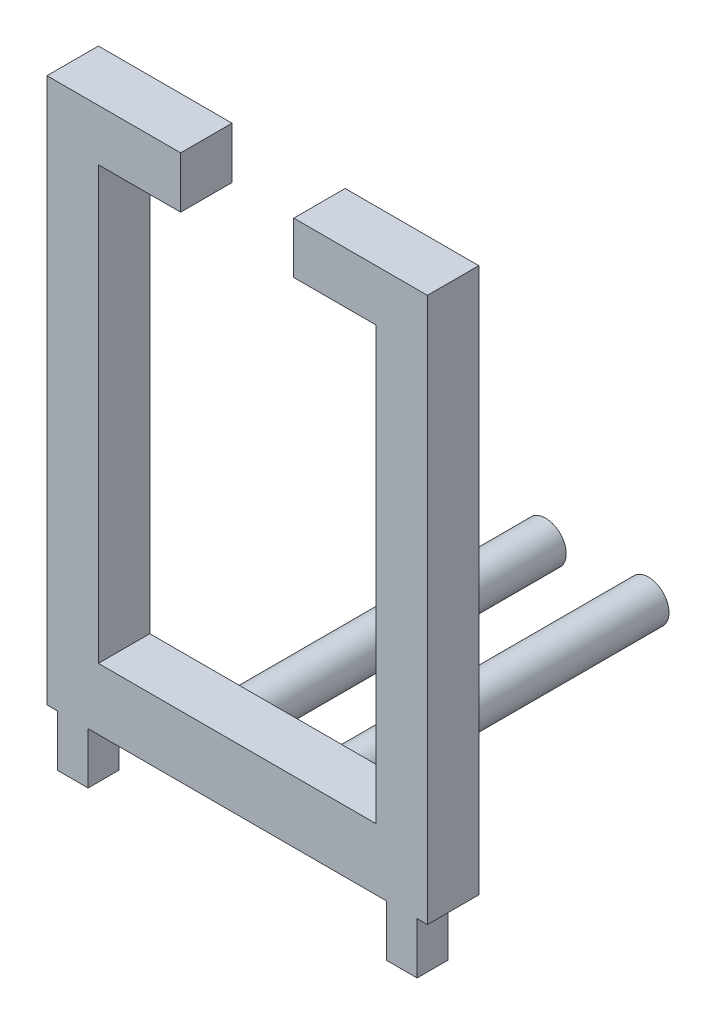
SolidWorks part; units mm, degrees
ref_plane "前视基准面" through (0, 0, 0) normal (0, 0, 1) x (1, 0, 0)
ref_plane "上视基准面" through (0, 0, 0) normal (0, 1, 0) x (1, 0, 0)
ref_plane "右视基准面" through (0, 0, 0) normal (1, 0, 0) x (0, 0, -1)
sketch "草图1" plane through (0, 0, 0) normal (0, 1, 0) x (1, 0, 0)
  line L0 (-303.1504, -31.6586) -> (-303.1504, -28.6586)
  line L1 (-303.1504, -28.6586) -> (-300.1504, -28.6586)
  line L2 (-300.1504, -28.6586) -> (-300.1504, -31.6586)
  line L3 (-300.1504, -31.6586) -> (-303.1504, -31.6586)
  line L4 (-271.1504, -28.6586) -> (-268.1504, -28.6586)
  line L5 (-268.1504, -28.6586) -> (-268.1504, -31.6586)
  line L6 (-268.1504, -31.6586) -> (-271.1504, -31.6586)
  line L7 (-271.1504, -31.6586) -> (-271.1504, -28.6586)
  point P6 (0, 0)
  point P9 (0, 0)
  dimension "D1" = 29
extrude "凸台-拉伸1" add sketch "草图1" along normal blind 5
sketch "草图2" plane through (0, 5, 0) normal (0, 1, 0) x (1, 0, 0)
  line L0 (-304.1504, -26.6586) -> (-299.1504, -26.6586)
  line L1 (-299.1504, -26.6586) -> (-299.1504, -31.6586)
  line L2 (-299.1504, -31.6586) -> (-304.1504, -31.6586)
  line L3 (-304.1504, -31.6586) -> (-304.1504, -26.6586)
  line L4 (-300.1504, -28.6586) -> (-303.1504, -28.6586) construction
  line L5 (-272.1504, -26.6586) -> (-267.1504, -26.6586)
  line L6 (-267.1504, -26.6586) -> (-267.1504, -31.6586)
  line L7 (-267.1504, -31.6586) -> (-272.1504, -31.6586)
  line L8 (-272.1504, -31.6586) -> (-272.1504, -26.6586)
  line L9 (-271.1504, -31.6586) -> (-268.1504, -31.6586) construction
  line L10 (-271.1504, -31.6586) -> (-268.1504, -31.6586) construction
  point P2 (-301.6504, -26.6586)
  point P7 (-301.6504, -28.6586)
  point P13 (-269.6504, -31.6586)
  point P17 (-269.6504, -31.6586)
extrude "凸台-拉伸2" add sketch "草图2" along normal blind 6
sketch "草图4" plane through (0, 11, 0) normal (0, 1, 0) x (1, 0, 0)
  line L0 (-304.1504, -26.6586) -> (-267.1504, -26.6586)
  line L1 (-267.1504, -26.6586) -> (-267.1504, -31.6586)
  line L2 (-267.1504, -31.6586) -> (-304.1504, -31.6586)
  line L3 (-304.1504, -31.6586) -> (-304.1504, -26.6586)
extrude "凸台-拉伸3" add sketch "草图4" against normal blind 6
sketch "草图5" plane through (0, 0, 26.6586) normal (0, 0, -1) x (-1, 0, 0)
  circle A0 centre (280.6505, 8.0197) radius 2
  circle A1 centre (290.6504, 7.9803) radius 2
  dimension "D1" = 9.9999
extrude "凸台-拉伸4" add sketch "草图5" along normal blind 30
sketch "草图6" plane through (0, 11, 0) normal (0, 1, 0) x (1, 0, 0)
  line L0 (-267.1504, -31.6586) -> (-272.1504, -31.6586)
  line L1 (-304.1504, -31.6586) -> (-267.1504, -31.6586) construction
  line L2 (-272.1504, -31.6586) -> (-272.1504, -26.6586)
  line L3 (-267.1504, -26.6586) -> (-304.1504, -26.6586) construction
  line L4 (-272.1504, -26.6586) -> (-267.1504, -26.6586)
  line L5 (-267.1504, -26.6586) -> (-267.1504, -31.6586)
  line L6 (-304.1504, -26.6586) -> (-299.1504, -26.6586)
  line L7 (-299.1504, -26.6586) -> (-299.1504, -31.6586)
  line L8 (-299.1504, -31.6586) -> (-304.1504, -31.6586)
  line L9 (-304.1504, -31.6586) -> (-304.1504, -26.6586)
  dimension "D1" = 27
extrude "凸台-拉伸5" add sketch "草图6" along normal blind 47
sketch "草图7" plane through (-299.1504, 0, 0) normal (1, 0, 0) x (0, 0, -1)
  line L0 (-31.6586, 58) -> (-26.6586, 58)
  line L1 (-26.6586, 58) -> (-26.6586, 53)
  line L2 (-26.6586, 58) -> (-26.6586, 11) construction
  line L3 (-26.6586, 53) -> (-31.6586, 53)
  line L4 (-31.6586, 58) -> (-31.6586, 11) construction
  line L5 (-31.6586, 53) -> (-31.6586, 58)
  point P7 (0, 0)
extrude "凸台-拉伸6" add sketch "草图7" along normal blind 8
sketch "草图8" plane through (-272.1504, 0, 0) normal (-1, 0, 0) x (0, 0, 1)
  line L0 (26.6586, 58) -> (31.6586, 58)
  line L1 (31.6586, 58) -> (31.6586, 53)
  line L2 (31.6586, 58) -> (31.6586, 11) construction
  line L3 (31.6586, 53) -> (26.6586, 53)
  line L4 (26.6586, 58) -> (26.6586, 11) construction
  line L5 (26.6586, 53) -> (26.6586, 58)
extrude "凸台-拉伸7" add sketch "草图8" along normal blind 8
